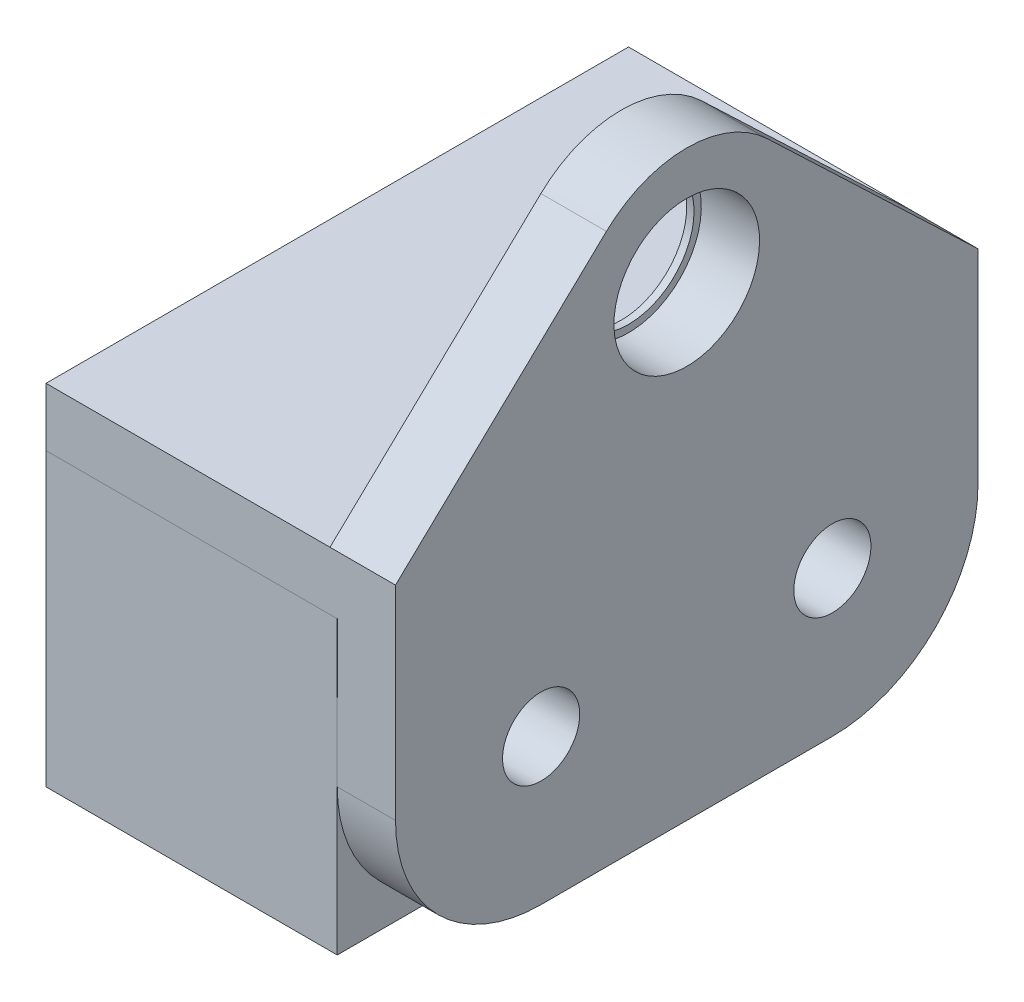
SolidWorks part; units mm, degrees
material "ABS"
ref_plane "Спереди" through (0, 0, 0) normal (0, 0, 1) x (1, 0, 0)
ref_plane "Сверху" through (0, 0, 0) normal (0, 1, 0) x (1, 0, 0)
ref_plane "Справа" through (0, 0, 0) normal (1, 0, 0) x (0, 0, -1)
sketch "Эскиз2" plane through (0, 0, 0) normal (0, 0, 1) x (1, 0, 0)
  line L1 (10, -10) -> (-10, -10)
  line L2 (10, -10) -> (10, 10)
  line L3 (10, 10) -> (-10, 10)
  line L4 (-10, -10) -> (-10, 10)
  line L5 (10, -10) -> (-10, 10) construction
  line L6 (10, 10) -> (-10, -10) construction
  point P0 (0, 0)
  dimension "D1" = 20
  dimension "D2" = 20
extrude "Бобышка-Вытянуть1" add sketch "Эскиз2" along normal mid plane 40
sketch "Эскиз3" plane through (10, 0, 0) normal (1, 0, 0) x (0, 0, -1)
  line L1 (-20, 10) -> (20, 10)
  line L2 (-20, 10) -> (20, 10) construction
  line L3 (-20, 10) -> (-20, 14)
  line L4 (-20, 14) -> (20, 14)
  line L5 (-20, 10) -> (20, 10)
  line L6 (20, 10) -> (20, 14)
  line L7 (20, -10) -> (20, 10)
  line L8 (20, 10) -> (-20, 10)
  line L9 (-20, 10) -> (-20, -10)
  line L10 (-20, -10) -> (20, -10)
  line L11 (20, -10) -> (20, 10)
  line L12 (0, 14) -> (0, 10) construction
  line L13 (-20, 10) -> (-20, -10)
  line L14 (-20, -10) -> (20, -10)
  line L15 (-20, 12) -> (20, 12) construction
  point P224 (0, 12)
  dimension "D1" = 4
  dimension "D3" = 0
extrude "Бобышка-Вытянуть2" add sketch "Эскиз3" along normal blind 4 separate body
hole_wizard "Отверстие с зазором M51" positions "Эскиз4" profile "Эскиз5" hole size "M5" standard "ISO" end condition up to next
sketch "Эскиз4" plane through (14, 0, 0) normal (1, 0, 0) x (0, 0, -1)
  point P0 (-10, 0)
  point P2 (10, 0)
  dimension "D1" = 20
  dimension "D2" = 10
sketch "Эскиз5" plane through (14, 0, 10) normal (0, 1, 0) x (0, 0, -1)
  line L0 (0, 0) -> (0, 24)
  line L1 (0, 24) -> (2.65, 24)
  line L2 (2.65, 24) -> (2.65, 0)
  line L5 (2.65, 0) -> (0, 0)
  line L11 (0, -6.35) -> (0, 107.95) construction
  dimension "Диаметр сквозного отверстия" = 5.3
  dimension "Глубина сквозного отверстия" = 24
sketch "Эскиз6" plane through (10, 0, 0) normal (-1, 0, 0) x (0, 0, 1)
  line L0 (-20, -10) -> (-20, 14) construction
  line L1 (20, 14) -> (-20, 14)
  line L3 (20, 14) -> (20, 10)
  line L5 (20, 10) -> (-20, 10)
  line L6 (-20, 14) -> (-20, 10)
  line L7 (0, 10) -> (0, 14) construction
  line L8 (20, 12) -> (-20, 12) construction
  point P242 (0, 12)
  dimension "D1" = 4
extrude "Бобышка-Вытянуть3" add sketch "Эскиз6" along normal blind 20
sketch "Эскиз7" plane through (0, 10, 0) normal (0, -1, 0) x (1, 0, 0)
  line L0 (0, 0) -> (-50000, 0) construction
  line L1 (-3.05, 8) -> (3.05, 8)
  line L2 (-3.05, 8) -> (-3.05, 16)
  line L3 (-3.05, 16) -> (3.05, 16)
  line L4 (3.05, 8) -> (3.05, 16)
  line L5 (0, 16) -> (0, 8) construction
  line L6 (-3.05, 12) -> (3.05, 12) construction
  line L7 (-3.05, -12) -> (3.05, -12) construction
  line L8 (0, -16) -> (0, -8) construction
  line L9 (3.05, -8) -> (3.05, -16)
  line L10 (-3.05, -16) -> (3.05, -16)
  line L11 (-3.05, -8) -> (-3.05, -16)
  line L12 (-3.05, -8) -> (3.05, -8)
  point P14 (0, -12)
  point P56 (0, 12)
  dimension "D1" = 6.1
  dimension "D2" = 8
  dimension "D3" = 12
extrude "Бобышка-Вытянуть4" add sketch "Эскиз7" along normal blind 3
chamfer "Фаска1" distance 1 angle 45 4 edges at (-3.05, 7, 12) (3.05, 7, 12) (3.05, 7, -12) (-3.05, 7, -12)
sketch "Эскиз8" plane through (14, 0, 0) normal (1, 0, 0) x (0, 0, -1)
  line L0 (-20, 14) -> (-5.5172, 27.7931)
  line L1 (5.5172, 27.7931) -> (20, 14)
  line L2 (-20, 14) -> (20, 14) construction
  circle A0 centre (0, 22) radius 5
  arc A1 (-5.5172, 27.7931) -> (5.5172, 27.7931) centre (0, 22) cw
  line M8 (20, 14) -> (-20, 14)
  dimension "D1" = 10
  dimension "D2" = 3
  dimension "D3" = 3
extrude "Бобышка-Вытянуть5" add sketch "Эскиз8" against normal blind 4.5 contours A1 L0 L1 A0 M8
sketch "Эскиз9" plane through (9.5, 0, 0) normal (-1, 0, 0) x (0, 0, 1)
  circle A0 centre (0, 22) radius 5 construction
  circle A1 centre (0, 22) radius 5
  circle A2 centre (0, 22) radius 4.5
  dimension "D1" = 0.5
extrude "Бобышка-Вытянуть6" add sketch "Эскиз9" against normal offset from surface (0.5 mm away) 4 up to face at (14, 0, 7.35)
fillet "Скругление1" radius 10 2 edges at (12, -10, 20) (12, -10, -20)
